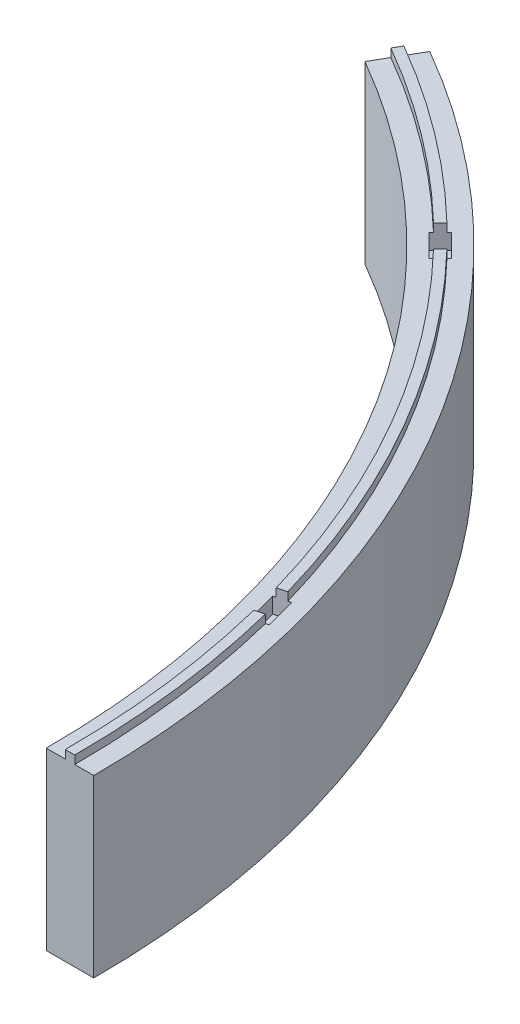
SolidWorks part; units mm, degrees
ref_plane "Ebene vorne" through (0, 0, 0) normal (0, 0, 1) x (1, 0, 0)
ref_plane "Ebene oben" through (0, 0, 0) normal (0, 1, 0) x (1, 0, 0)
ref_plane "Ebene rechts" through (0, 0, 0) normal (1, 0, 0) x (0, 0, -1)
sketch "Skizze1" plane through (0, 0, 0) normal (0, 1, 0) x (1, 0, 0)
  line L0 (0, 0) -> (290, 0) construction
  line L1 (290, 0) -> (0, 0) construction
  line L2 (0, 0) -> (145, 251.1474) construction
  line L3 (137.5, 238.157) -> (145, 251.1474)
  line L4 (275, 0) -> (290, 0)
  arc A0 (145, 251.1474) -> (290, 0) centre (0, 0) cw
  arc A1 (137.5, 238.157) -> (275, 0) centre (0, 0) cw
  dimension "D1" = 290
  dimension "D2" = 275
  dimension "D3" = 60
extrude "Aufsatz-Linear austragen1" add sketch "Skizze1" along normal blind 55.4
sketch "Skizze2" plane through (0, 55.4, 0) normal (0, 1, 0) x (1, 0, 0)
  line L0 (275, 0) -> (290, 0) construction
  line L1 (145, 251.1474) -> (137.5, 238.157) construction
  line L2 (140.5, 243.3531) -> (142, 245.9512)
  line L3 (281, 0) -> (284, 0)
  arc A0 (284, 0) -> (142, 245.9512) centre (0, 0) ccw
  arc A1 (281, 0) -> (140.5, 243.3531) centre (0, 0) ccw
  dimension "D1" = 3
  dimension "D2" = 6
extrude "Aufsatz-Linear austragen2" add sketch "Skizze2" along normal blind 2.6
sketch "Skizze3" plane through (0, 58, 0) normal (0, 1, 0) x (1, 0, 0)
  line L0 (281, 0) -> (284, 0) construction
  line L1 (142, 245.9512) -> (140.5, 243.3531) construction
  line L2 (0, 0) -> (272.874, 73.1164) construction
  line L3 (0, 0) -> (199.7577, 199.7577) construction
  line L4 (275, 0) -> (281, 0) construction
  line L5 (269.1651, 77.299) -> (273.9948, 78.5931)
  line L6 (273.9948, 78.5931) -> (276.583, 68.9338)
  line L7 (276.583, 68.9338) -> (271.7533, 67.6397)
  line L8 (271.7533, 67.6397) -> (269.1651, 77.299)
  line L9 (269.1651, 77.299) -> (276.583, 68.9338) construction
  line L10 (194.4544, 201.5254) -> (197.9899, 205.061)
  line L11 (197.9899, 205.061) -> (205.061, 197.9899)
  line L12 (205.061, 197.9899) -> (201.5254, 194.4544)
  line L13 (201.5254, 194.4544) -> (194.4544, 201.5254)
  line L14 (194.4544, 201.5254) -> (205.061, 197.9899) construction
  arc A0 (282.5, 0) -> (141.25, 244.6522) centre (0, 0) ccw construction
  point P14 (272.874, 73.1164)
  point P19 (199.7577, 199.7577)
  dimension "D1" = 30
  dimension "D2" = 15
  dimension "D3" = 5
  dimension "D4" = 10
  dimension "D5" = 5
  dimension "D6" = 5
extrude "Schnitt-Linear austragen1" cut sketch "Skizze3" against normal blind 7.5
sketch "Skizze4" plane through (0, 0, 0) normal (0, -1, 0) x (1, 0, 0)
  line L0 (145, -251.1474) -> (137.5, -238.157) construction
  line L1 (275, 0) -> (290, 0) construction
  line L2 (0, 0) -> (282.5, 0) construction
  line L3 (0, 0) -> (272.874, -73.1164) construction
  line L4 (0, 0) -> (199.7577, -199.7577) construction
  arc A0 (141.25, -244.6522) -> (282.5, 0) centre (0, 0) ccw construction
  circle A1 centre (199.7577, -199.7577) radius 2.2
  circle A2 centre (272.874, -73.1164) radius 2.2
  dimension "D1" = 4.4
  dimension "D2" = 15
  dimension "D3" = 30
extrude "Schnitt-Linear austragen2" cut sketch "Skizze4" against normal blind 10
equation "\"D5@Skizze3\"=\"D4@Skizze3\"/2"
equation "\"D6@Skizze3\"=\"D5@Skizze3\""
